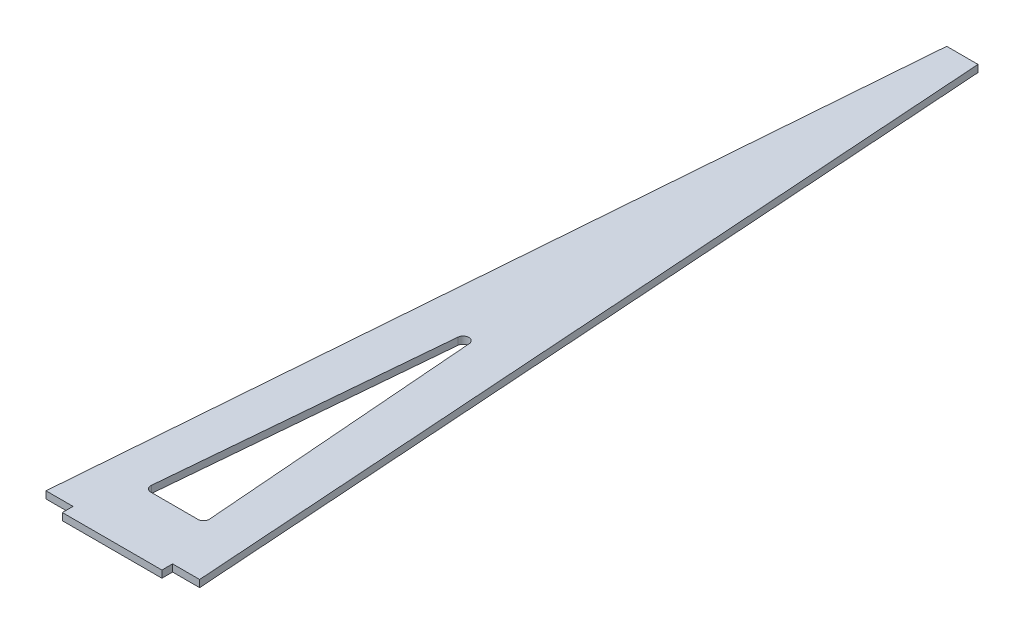
SolidWorks part; units mm, degrees
material "Balsa"
ref_plane "Front Plane" through (0, 0, 0) normal (0, 0, 1) x (1, 0, 0)
ref_plane "Top Plane" through (0, 0, 0) normal (0, 1, 0) x (1, 0, 0)
ref_plane "Right Plane" through (0, 0, 0) normal (1, 0, 0) x (0, 0, -1)
sketch "Sketch1" plane through (0, 0, 0) normal (0, 1, 0) x (1, 0, 0)
  line L0 (-1000, 0) -> (0, 0) construction
  line L1 (0, 0) -> (0, -27.3326) construction
  line L2 (0, 0) -> (-38.1, 0)
  line L3 (-38.1, 0) -> (-5.08, 372.872)
  line L4 (-5.08, 372.872) -> (0, 372.872)
  line L5 (0, 372.872) -> (0, 0) construction
  line L7 (0, 0) -> (38.1, 0)
  line L8 (38.1, 0) -> (8.89, 372.872)
  line L9 (8.89, 372.872) -> (0, 372.872)
  point P2 (38.1, 0)
  dimension "D1" = 38.1
  dimension "D2" = 372.872
  dimension "D3" = 5.08
  dimension "D4" = 8.89
extrude "Boss-Extrude1" add sketch "Sketch1" along normal blind 3.175
sketch "Sketch2" plane through (0, 3.175, 0) normal (0, 1, 0) x (1, 0, 0)
  line L4 (13.3792, 22.86) -> (0.9379, 181.6755)
  line L5 (13.3792, 22.86) -> (0.9379, 181.6755)
  line L8 (0.9379, 181.6755) -> (-13.1262, 22.86)
  line L9 (-13.1262, 22.86) -> (13.3792, 22.86)
  line L11 (0.9379, 181.6755) -> (-13.1262, 22.86)
  line L12 (-13.1262, 22.86) -> (13.3792, 22.86)
  dimension "D1" = 22.86
extrude "Cut-Extrude1" cut sketch "Sketch2" against normal blind 3.175
fillet "Fillet1" radius 2.54 3 edges at (0.9379, 1.5875, -181.6755) (13.3792, 1.5875, -22.86) (-13.1262, 1.5875, -22.86)
sketch "Sketch3" plane through (0, 0, 0) normal (0, 0, 1) x (1, 0, 0)
  line L0 (0, 3.175) -> (0, 0) construction
  line L1 (-38.1, 3.175) -> (38.1, 3.175) construction
  line L2 (-38.1, 0) -> (38.1, 0) construction
  line L3 (-22.225, 3.175) -> (22.225, 3.175)
  line L4 (-22.225, 3.175) -> (-22.225, 0)
  line L5 (-22.225, 0) -> (22.225, 0)
  line L6 (22.225, 3.175) -> (22.225, 0)
  line L7 (-22.225, 3.175) -> (22.225, 0) construction
  line L8 (-22.225, 0) -> (22.225, 3.175) construction
  point P5 (0, 1.5875)
  dimension "D1" = 44.45
extrude "Boss-Extrude2" add sketch "Sketch3" along normal blind 4.7625
sketch "Sketch4" plane through (0, 3.175, 0) normal (0, 1, 0) x (1, 0, 0)
  line L0 (-5.08, 372.872) -> (-34.29, 0)
  line L1 (-38.1, 0) -> (-22.225, 0) construction
  line L2 (-34.29, 0) -> (-38.1, 0)
  line L3 (-38.1, 0) -> (-5.08, 372.872)
  line L4 (38.1, 0) -> (8.89, 372.872)
  line L5 (8.89, 372.872) -> (34.29, 0)
  line L6 (22.225, 0) -> (38.1, 0) construction
  line L7 (34.29, 0) -> (38.1, 0)
  dimension "D1" = 3.81
  dimension "D2" = 3.81
extrude "Cut-Extrude2" cut sketch "Sketch4" against normal through all
